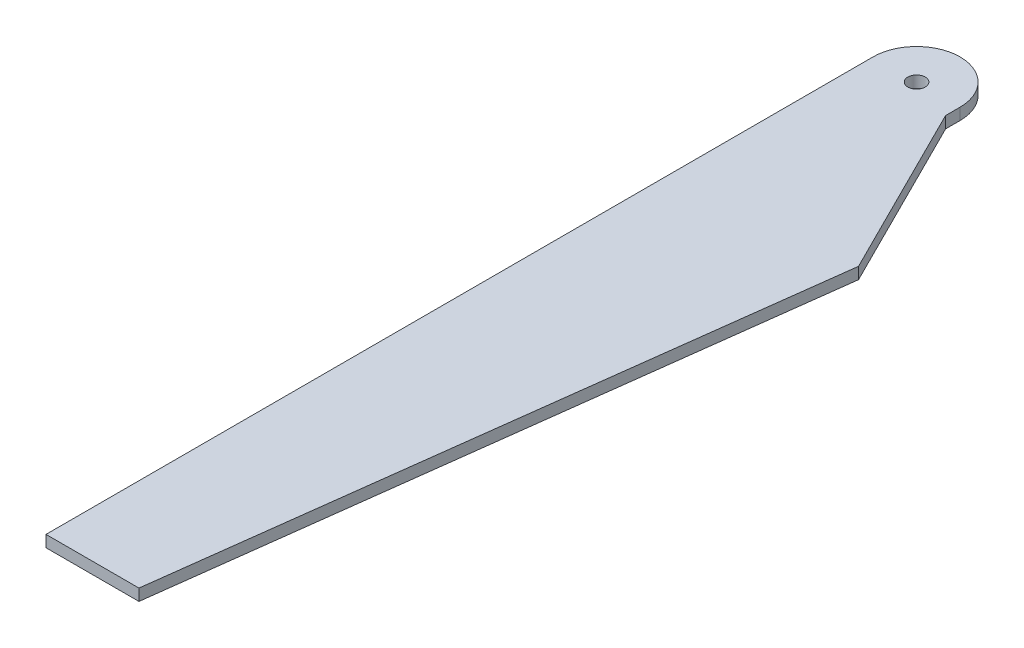
SolidWorks part; units mm, degrees
ref_plane "Alzado" through (0, 0, 0) normal (0, 0, 1) x (1, 0, 0)
ref_plane "Planta" through (0, 0, 0) normal (0, 1, 0) x (1, 0, 0)
ref_plane "Vista lateral" through (0, 0, 0) normal (1, 0, 0) x (0, 0, -1)
sketch "Croquis1" plane through (0, 0, 0) normal (0, 1, 0) x (1, 0, 0)
  line L0 (0, 0) -> (0, 77.0373) construction
  line L1 (0, 0) -> (83.7433, 0) construction
  line L2 (-30, 0) -> (-30, 79.0238)
  line L4 (-15, 79.0238) -> (-15, 76.5238)
  line L7 (-30, -63.4762) -> (-30, 0)
  line L9 (-15, 79.0238) -> (-15, 76.5238)
  line L12 (-15, 76.5238) -> (0, 46.5238)
  line L13 (-13.9831, -63.4762) -> (0, 46.5238)
  line L15 (-30, -63.4762) -> (-13.9831, -63.4762)
  circle A0 centre (-22.5, 79.0238) radius 1.5
  arc A1 (-15, 79.0238) -> (-30, 79.0238) centre (-22.5, 79.0238) ccw
  dimension "D5" = 7.5
extrude "Saliente-Extruir1" add sketch "Croquis1" along normal blind 2
